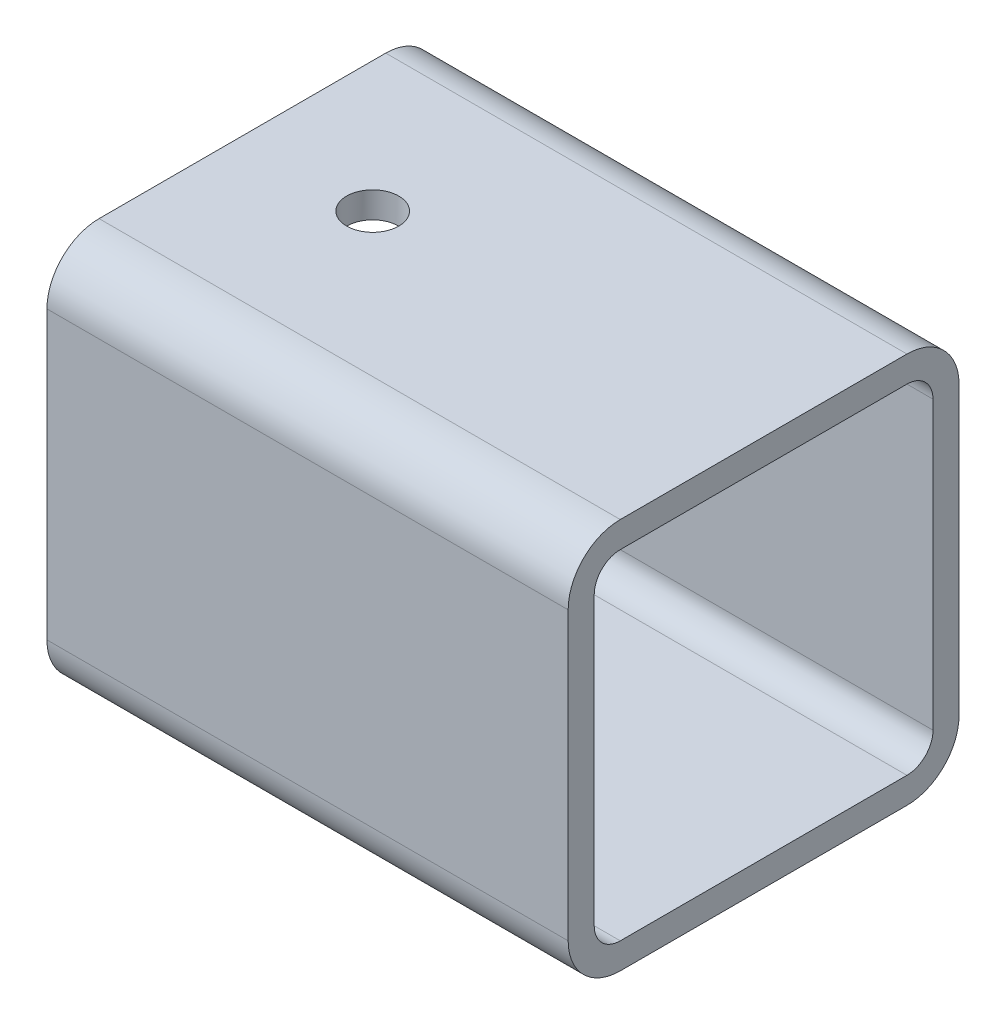
SolidWorks part; units mm, degrees
ref_plane "前视基准面" through (0, 0, 0) normal (0, 0, 1) x (1, 0, 0)
ref_plane "上视基准面" through (0, 0, 0) normal (0, 1, 0) x (1, 0, 0)
ref_plane "右视基准面" through (0, 0, 0) normal (1, 0, 0) x (0, 0, -1)
sketch "草图1" plane through (0, 0, 0) normal (1, 0, 0) x (0, 0, -1)
  line L0 (-11, -13) -> (11, -13)
  line L1 (-11, -15) -> (11, -15)
  line L2 (-15, -11) -> (-15, 11)
  line L3 (-11, 15) -> (11, 15)
  line L4 (15, -11) -> (15, 11)
  line L5 (13, -11) -> (13, 11)
  line L6 (-11, 13) -> (11, 13)
  line L7 (-13, -11) -> (-13, 11)
  arc A0 (-11, -15) -> (-15, -11) centre (-11, -11) cw
  arc A1 (11, -15) -> (15, -11) centre (11, -11) ccw
  arc A2 (11, 15) -> (15, 11) centre (11, 11) cw
  arc A3 (-15, 11) -> (-11, 15) centre (-11, 11) cw
  arc A4 (11, -13) -> (13, -11) centre (11, -11) ccw
  arc A5 (11, 13) -> (13, 11) centre (11, 11) cw
  arc A6 (-13, 11) -> (-11, 13) centre (-11, 11) cw
  arc A7 (-11, -13) -> (-13, -11) centre (-11, -11) cw
extrude "凸台-拉伸1" add sketch "草图1" along normal mid plane 40
sketch "草图2" plane through (0, 0, 0) normal (0, 1, 0) x (1, 0, 0)
  line L1 (-20, 11) -> (-20, -11) construction
  circle A0 centre (-10, 0) radius 2
  dimension "D1" = 4
  dimension "D2" = 10
extrude "切除-拉伸1" cut sketch "草图2" against normal through all both and the other way through all
